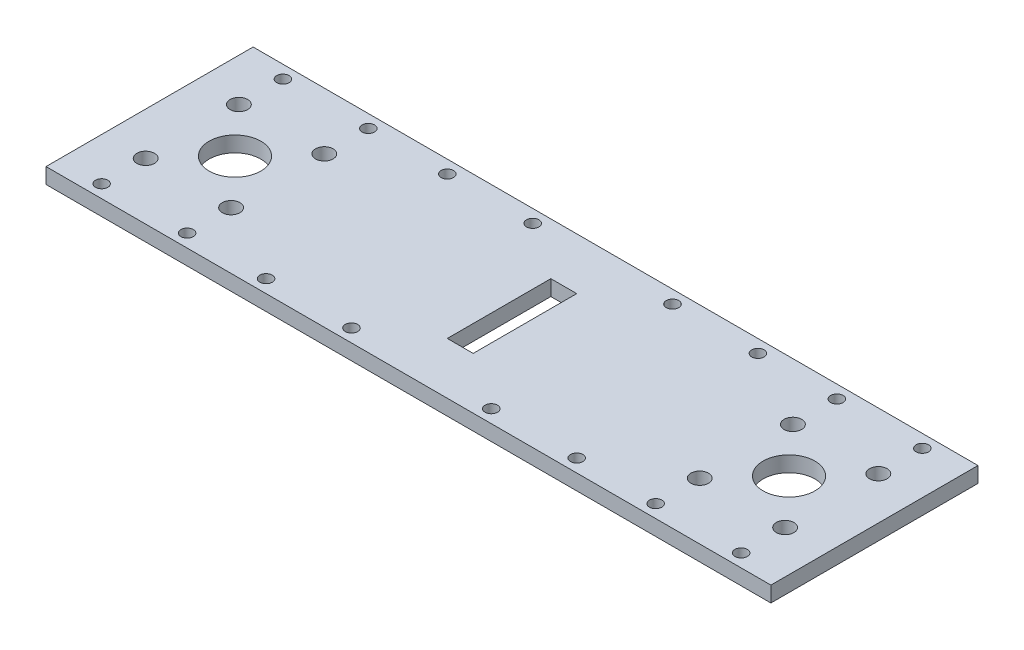
SolidWorks part; units mm, degrees
ref_plane "Front Plane" through (0, 0, 0) normal (0, 0, 1) x (1, 0, 0)
ref_plane "Top Plane" through (0, 0, 0) normal (0, 1, 0) x (1, 0, 0)
ref_plane "Right Plane" through (0, 0, 0) normal (1, 0, 0) x (0, 0, -1)
sketch "Sketch1" plane through (0, 0, 0) normal (0, 1, 0) x (1, 0, 0)
  line L0 (0, 0) -> (0, -14.43) construction
  line L1 (-70, 20) -> (70, 20)
  line L2 (-70, 20) -> (-70, -20)
  line L3 (-70, -20) -> (70, -20)
  line L4 (70, 20) -> (70, -20)
  line L5 (-70, 20) -> (70, -20) construction
  line L6 (-70, -20) -> (70, 20) construction
  line L7 (0, 0) -> (6.508, 0) construction
  line L8 (-2.5, 10) -> (2.5, 10)
  line L9 (-2.5, 10) -> (-2.5, -10)
  line L10 (-2.5, -10) -> (2.5, -10)
  line L11 (2.5, 10) -> (2.5, -10)
  line L12 (-2.5, 10) -> (2.5, -10) construction
  line L13 (-2.5, -10) -> (2.5, 10) construction
  line L15 (-33.5, 20) -> (33.5, 20)
  line L16 (-33.5, 20) -> (-33.5, -20)
  line L17 (-33.5, -20) -> (33.5, -20)
  line L18 (33.5, 20) -> (33.5, -20)
  circle A0 centre (-53.5, 0) radius 5
  circle A1 centre (-61.75, 9) radius 1.7
  circle A7 centre (53.5, 0) radius 5
  circle A10 centre (-61.75, -17.5) radius 1.1976
  circle A18 centre (-45.25, 9) radius 1.7
  circle A19 centre (-45.25, -9) radius 1.7
  circle A20 centre (-61.75, -9) radius 1.7
  circle A21 centre (61.75, 9) radius 1.7
  circle A22 centre (45.25, 9) radius 1.7
  circle A23 centre (61.75, -9) radius 1.7
  circle A24 centre (45.25, -9) radius 1.7
  circle A25 centre (-45.25, -17.5) radius 1.1976
  circle A26 centre (-45.25, 17.5) radius 1.1976
  circle A27 centre (-61.75, 17.5) radius 1.1976
  circle A28 centre (45.25, -17.5) radius 1.1976
  circle A29 centre (61.75, -17.5) radius 1.1976
  circle A30 centre (45.25, 17.5) radius 1.1976
  circle A31 centre (61.75, 17.5) radius 1.1976
  circle A41 centre (-30, -17.5) radius 1.2
  circle A42 centre (-13.5, -17.5) radius 1.2
  circle A43 centre (-30, 17.5) radius 1.2
  circle A44 centre (-13.5, 17.5) radius 1.2
  circle A45 centre (30, 17.5) radius 1.2
  circle A46 centre (13.5, 17.5) radius 1.2
  circle A47 centre (13.5, -17.5) radius 1.2
  circle A48 centre (30, -17.5) radius 1.2
  point P0 (0, 0)
  dimension "D3" = 10
  dimension "D4" = 16.5
  dimension "D5" = 9
  dimension "D6" = 8.25
  dimension "D9" = 5
  dimension "D11" = 20
  dimension "D12" = 2
  dimension "D13" = 2.3951
  dimension "D14" = 8.25
  dimension "D15" = 2.5
  dimension "D17" = 36.5
  dimension "D18" = 2.4
  dimension "D19" = 16.5
  dimension "D20" = 2.5
  dimension "D21" = 2.5
  dimension "D22" = 27
  dimension "D1" = 140
  dimension "D2" = 40
  dimension "D10" = 20
  dimension "D16" = 36.5
  dimension "D7" = 2
  dimension "D8" = 2
extrude "Boss-Extrude2" add sketch "Sketch1" along normal blind 3 contours L18 L1 L16 L3 A47 A46 A45 A43 A42 A41 L8 L11 L10 L9 A44 A48 | L16 L1 L2 L3 A26 A25 A20 A19 A18 A10 A1 A0 A27 | L1 L18 L3 L4 A31 A30 A28 A23 A21 A7 A22 A24 A29
